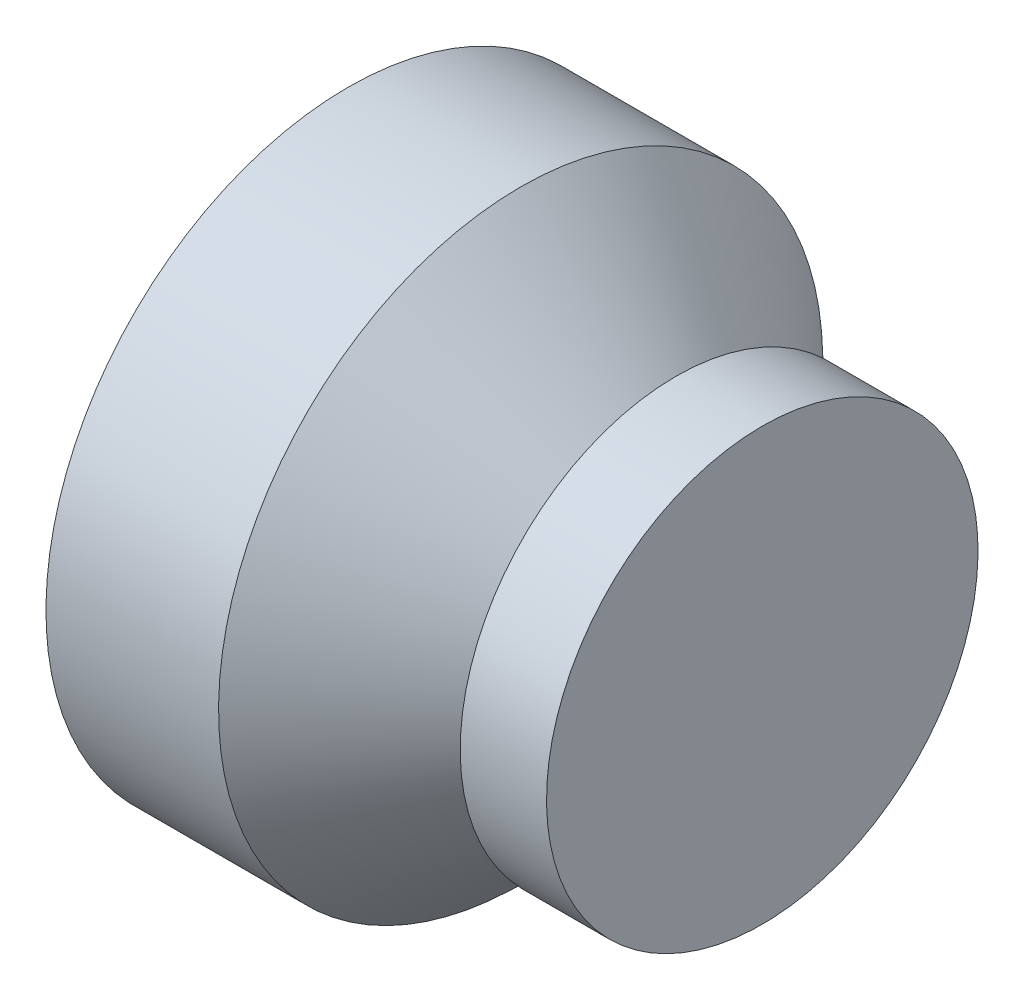
SolidWorks part; units mm, degrees
ref_plane "Front Plane" through (0, 0, 0) normal (0, 0, 1) x (1, 0, 0)
ref_plane "Top Plane" through (0, 0, 0) normal (0, 1, 0) x (1, 0, 0)
ref_plane "Right Plane" through (0, 0, 0) normal (1, 0, 0) x (0, 0, -1)
sketch "Sketch1" plane through (0, 0, 0) normal (0, 0, 1) x (1, 0, 0)
  line L0 (-119, 0) -> (-143, 0) construction
  line L1 (143, -52.5) -> (-143, -52.5) construction
  line L2 (143, -52.5) -> (143, 52.5) construction
  line L3 (143, 52.5) -> (-143, 52.5) construction
  line L4 (-143, -52.5) -> (-143, 52.5) construction
  line L5 (143, -52.5) -> (-143, 52.5) construction
  line L6 (143, 52.5) -> (-143, -52.5) construction
  line L7 (143, 52.5) -> (-119, 52.5) construction
  line L8 (143, 52.5) -> (143, -52.5) construction
  line L9 (143, -52.5) -> (-119, -52.5) construction
  line L10 (-119, 52.5) -> (-119, -52.5) construction
  line L11 (143, 52.5) -> (-119, -52.5) construction
  line L12 (143, -52.5) -> (-119, 52.5) construction
  line L13 (-119, -52.5) -> (-143, -52.5) construction
  line L14 (-119, -52.5) -> (-119, -47.5) construction
  line L15 (-119, -47.5) -> (-143, -47.5) construction
  line L16 (-143, -52.5) -> (-143, -47.5) construction
  line L17 (-119, -52.5) -> (-143, -47.5) construction
  line L18 (-119, -47.5) -> (-143, -52.5) construction
  line L19 (-119, 17.5) -> (-143, 17.5) construction
  line L20 (-119, 17.5) -> (-119, -17.5) construction
  line L21 (-119, -17.5) -> (-143, -17.5) construction
  line L22 (-143, 17.5) -> (-143, -17.5) construction
  line L23 (-119, 17.5) -> (-143, -17.5) construction
  line L24 (-119, -17.5) -> (-143, 17.5) construction
  line L25 (-119, 0) -> (-119, 12.5) construction
  line L26 (-133, 17.5) -> (-143, 17.5)
  line L27 (-119, 17.5) -> (-119, 0)
  line L28 (-119, 0) -> (-143, 0)
  line L29 (-143, 17.5) -> (-143, 0)
  line L30 (-119, 17.5) -> (-143, 0) construction
  line L31 (-119, 0) -> (-143, 17.5) construction
  line L32 (-143, 17.5) -> (-133, 17.5) construction
  line L33 (-119, 12.5) -> (-124, 12.5)
  line L34 (-119, 12.5) -> (-119, 0)
  line L35 (-119, 0) -> (-124, 0)
  line L36 (-124, 12.5) -> (-124, 9)
  line L37 (-119, 12.5) -> (-124, 0) construction
  line L38 (-119, 0) -> (-124, 12.5) construction
  line L39 (-124, 0) -> (-124, 9) construction
  line L40 (-124, 9) -> (-133, 17.5)
  line L41 (-124, 3.6458) -> (-124, 0)
  point P0 (0, 0)
  point P8 (12, 0)
  point P11 (-131, -50)
  point P16 (-131, 0)
  point P20 (-131, 8.75)
  point P23 (-121.5, 6.25)
  point P27 (0, 0)
  point P28 (0, 0)
  point P29 (0, 0)
  dimension "D1" = 262
  dimension "D2" = 286
  dimension "D3" = 105
  dimension "D4" = 5
  dimension "D5" = 35
  dimension "D6" = 35
  dimension "D7" = 12.5
  dimension "D8" = 5
  dimension "D9" = 10
  dimension "D10" = 9
revolve "Revolve2" add sketch "Sketch1" angle 360 about L28
